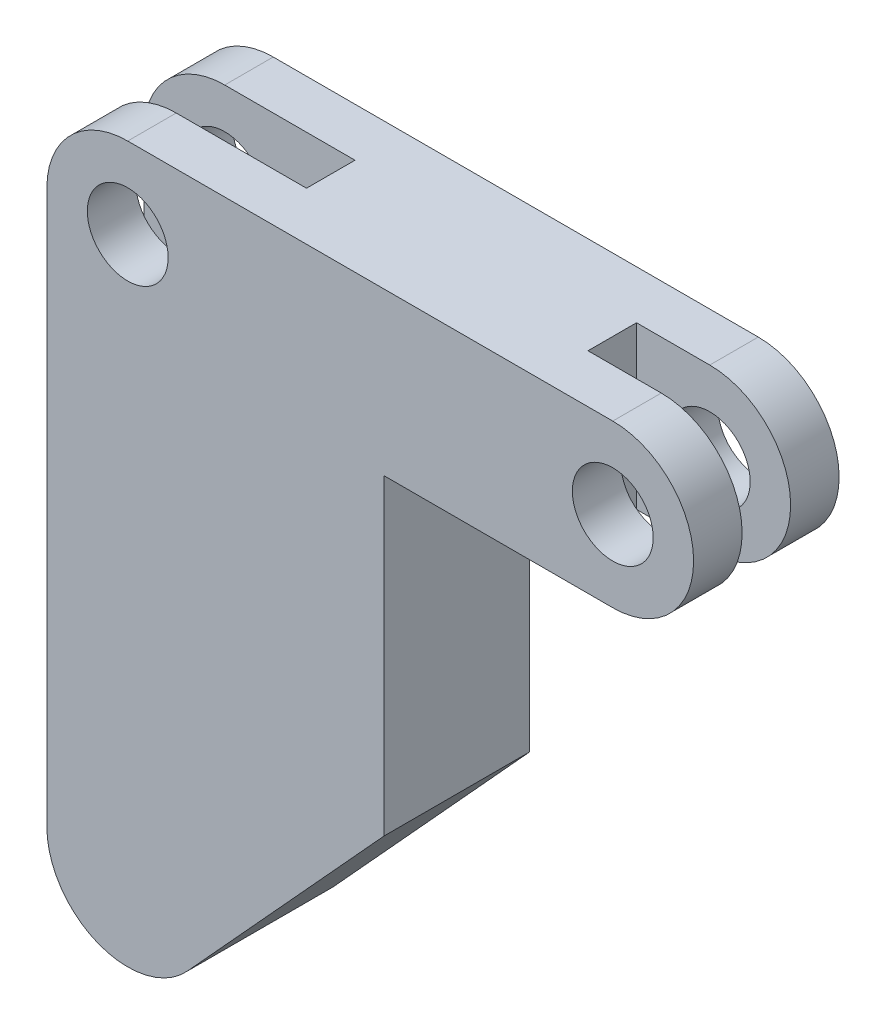
SolidWorks part; units mm, degrees
ref_plane "Front Plane" through (0, 0, 0) normal (0, 0, 1) x (1, 0, 0)
ref_plane "Top Plane" through (0, 0, 0) normal (0, 1, 0) x (1, 0, 0)
ref_plane "Right Plane" through (0, 0, 0) normal (1, 0, 0) x (0, 0, -1)
sketch "Sketch1" plane through (0, 0, 0) normal (0, 0, 1) x (1, 0, 0)
  line L0 (-15, 0) -> (15, 0) construction
  line L1 (-15, 5) -> (15, 5)
  line L2 (-15, -5) -> (15, -5)
  line L3 (-20, 0) -> (-20, -34.2421)
  line L4 (-11.3082, -37.6141) -> (0.8543, -24.298)
  line L5 (0.8543, -24.298) -> (0.8543, 0)
  arc A0 (-15, 5) -> (-15, -5) centre (-15, 0) ccw
  arc A1 (15, -5) -> (15, 5) centre (15, 0) ccw
  arc A2 (-20, -34.2421) -> (-11.3082, -37.6141) centre (-15, -34.2421) ccw
  circle A3 centre (15, 0) radius 2.5
  circle A4 centre (-15, 0) radius 2.5
  point P2 (0, 0)
  dimension "D2" = 5
  dimension "D3" = 5
  dimension "D4" = 5
  dimension "D5" = 5
  dimension "D1" = 30
extrude "Boss-Extrude1" add sketch "Sketch1" along normal mid plane 9
sketch "Sketch2" plane through (0, 0, 0) normal (0, 0, 1) x (1, 0, 0)
  line L0 (-6.9423, 5) -> (-6.9423, -8.2652)
  line L1 (-15, 5) -> (15, 5) construction
  line L2 (-6.9423, -8.2652) -> (-20, -8.2652)
  line L3 (-20, 0) -> (-20, -34.2421) construction
  line L4 (-20, -8.2652) -> (-20, 0)
  line L5 (-20, 0) -> (-15, 5)
  line L6 (-15, 5) -> (-6.9423, 5)
  arc A1 (-15, 5) -> (-20, 0) centre (-15, 0) ccw
  arc A2 (-15, 5) -> (-20, 0) centre (-15, 0) ccw
  arc A3 (-20, 0) -> (-15, 5) centre (-15, 0) cw
extrude "Cut-Extrude1" cut sketch "Sketch2" against normal mid plane 3 contours L6 L5 L4 L2 L0
ref_plane "Plane1" through (0, 0, 0) normal (0, 0, 1) x (1, 0, 0)
sketch "Sketch4" plane through (0, 0, 0) normal (0, 0, 1) x (1, 0, 0)
  line L0 (-20, 0) -> (-15, 5)
  arc A0 (-15, 5) -> (-20, 0) centre (-15, 0) ccw construction
  arc A1 (-20, 0) -> (-15, 5) centre (-15, 0) cw
extrude "Cut-Extrude2" cut sketch "Sketch4" against normal mid plane 3
sketch "Sketch5" plane through (0, 0, 0) normal (0, 0, 1) x (1, 0, 0)
  line L0 (10.4687, 5) -> (10.4687, -5)
  line L1 (-15, 5) -> (15, 5) construction
  line L2 (10.4687, 5) -> (15, 5)
  line L3 (0.8543, -5) -> (15, -5) construction
  line L4 (10.4687, -5) -> (15, -5)
  arc A0 (15, 5) -> (15, -5) centre (15, 0) cw
  arc A1 (15, -5) -> (15, 5) centre (15, 0) ccw construction
extrude "Cut-Extrude3" cut sketch "Sketch5" against normal mid plane 3
